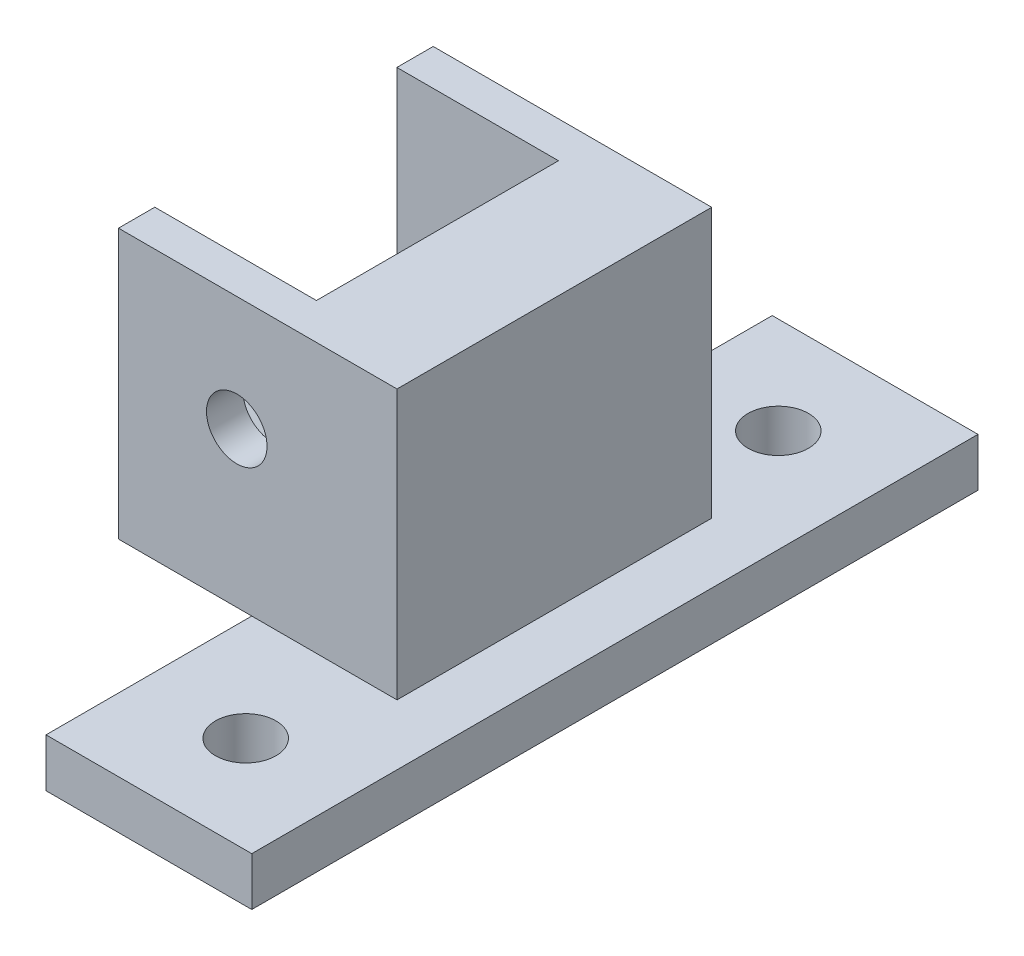
SolidWorks part; units mm, degrees
ref_plane "Front Plane" through (0, 0, 0) normal (0, 0, 1) x (1, 0, 0)
ref_plane "Top Plane" through (0, 0, 0) normal (0, 1, 0) x (1, 0, 0)
ref_plane "Right Plane" through (0, 0, 0) normal (1, 0, 0) x (0, 0, -1)
sketch "Sketch1" plane through (0, 0, 0) normal (0, 0, 1) x (1, 0, 0)
  line L0 (497.2339, 323.78) -> (526.4576, 323.78)
  line L1 (497.2339, 94.2304) -> (497.2339, 377.7498) construction
  line L2 (526.4576, 323.78) -> (526.4576, 352.0349)
  line L3 (526.4576, 352.0349) -> (497.2339, 352.0349)
  line L4 (497.2339, 352.0349) -> (497.2339, 323.78)
  line L5 (515.9742, 351.0105) -> (480.1928, 371.5786) construction
  line L6 (494.7056, 333.9388) -> (503.3159, 328.9895) construction
  line L7 (515.9742, 351.0105) -> (480.1928, 371.5786)
  line L8 (494.7056, 333.9388) -> (503.3159, 328.9895)
  line L9 (497.2339, 332.4855) -> (503.3159, 328.9895)
  line L10 (515.9742, 351.0105) -> (514.1922, 352.0349)
  arc A0 (520.1076, 347.199) -> (515.9742, 351.0105) centre (509.645, 340) ccw construction
  arc A1 (503.3159, 328.9895) -> (508.6898, 327.336) centre (509.645, 340) ccw construction
  arc A2 (508.6898, 327.336) -> (520.1076, 347.199) centre (509.645, 340) ccw construction
  arc A3 (520.1076, 347.199) -> (515.9742, 351.0105) centre (509.645, 340) ccw
  arc A4 (503.3159, 328.9895) -> (508.6898, 327.336) centre (509.645, 340) ccw
  arc A5 (508.6898, 327.336) -> (520.1076, 347.199) centre (509.645, 340) ccw
  arc A6 (503.3159, 328.9895) -> (508.6898, 327.336) centre (509.645, 340) ccw
  arc A7 (508.6898, 327.336) -> (520.1076, 347.199) centre (509.645, 340) ccw
  arc A8 (520.1076, 347.199) -> (515.9742, 351.0105) centre (509.645, 340) ccw
  dimension "D1" = 6.35
  dimension "D2" = 3.556
extrude "Boss-Extrude1" add sketch "Sketch1" against normal blind 29.21 contours A5 A4 L8 L4 L0 L2 L3 L7 A3
sketch "Sketch2" plane through (0, 0, -25.4) normal (0, 0, -1) x (-1, 0, 0)
  line L0 (-514.1922, 352.0349) -> (-497.2339, 352.0349)
  line L1 (-497.2339, 94.2304) -> (-497.2339, 377.7498) construction
  line L2 (-497.2339, 352.0349) -> (-497.2339, 332.4855)
  line L3 (-497.2339, 332.4855) -> (-503.3159, 328.9895)
  line L4 (-515.9742, 351.0105) -> (-514.1922, 352.0349)
  arc A0 (-503.3159, 328.9895) -> (-515.9742, 351.0105) centre (-509.645, 340) cw
  circle A1 centre (-509.645, 340) radius 3.175
extrude "Boss-Extrude2" add sketch "Sketch2" along normal blind 3.81
sketch "Sketch3" plane through (0, 0, 0) normal (0, 0, 1) x (1, 0, 0)
  line L0 (497.2339, 352.0349) -> (526.4576, 352.0349)
  line L1 (526.4576, 352.0349) -> (526.4576, 323.78)
  line L2 (526.4576, 323.78) -> (497.2339, 323.78)
  line L3 (497.2339, 323.78) -> (497.2339, 352.0349)
  circle A0 centre (509.645, 340) radius 3.175
  dimension "D1" = 6.35
extrude "Boss-Extrude4" add sketch "Sketch3" along normal blind 3.81 contours L3 L0 L1 L2 | A0
ref_plane "Plane1" through (0, 323.78, 0) normal (0, 1, 0) x (1, 0, 0)
sketch "Sketch4" plane through (0, 323.78, 0) normal (0, 1, 0) x (1, 0, 0)
  line L0 (526.4576, 29.21) -> (497.2339, 29.21) construction
  line L1 (511.2176, 50.8) -> (532.8076, 50.8)
  line L2 (511.2176, 50.8) -> (511.2176, -25.4)
  line L3 (511.2176, -25.4) -> (532.8076, -25.4)
  line L4 (532.8076, 50.8) -> (532.8076, -25.4)
  line L5 (497.2339, -3.81) -> (526.4576, -3.81) construction
  circle A0 centre (522.0126, 40.64) radius 3.175
  circle A1 centre (522.0126, -15.24) radius 3.175
  dimension "D5" = 10.795
  dimension "D7" = 10.795
  dimension "D9" = 6.35
  dimension "D10" = 6.35
  dimension "D1" = 21.59
  dimension "D2" = 21.59
  dimension "D3" = 21.59
  dimension "D4" = 6.35
  dimension "D6" = 10.16
  dimension "D8" = 10.16
extrude "Boss-Extrude5" add sketch "Sketch4" against normal blind 5.08
